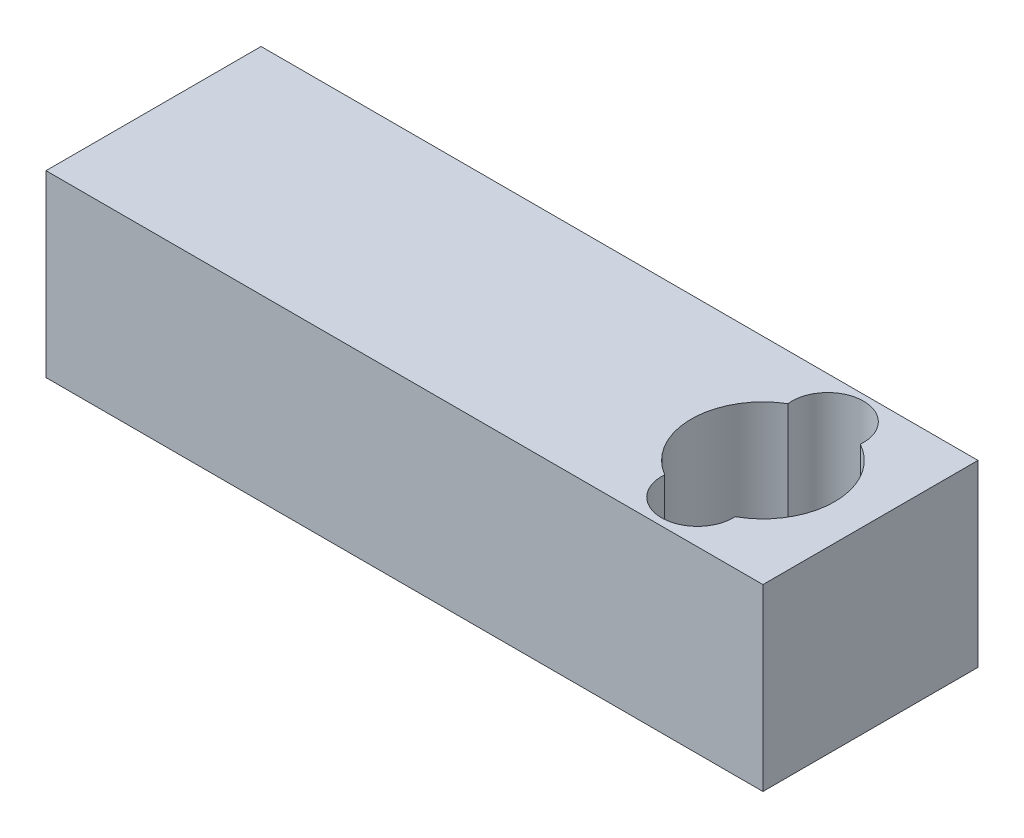
SolidWorks part; units mm, degrees
ref_plane "前视基准面" through (0, 0, 0) normal (0, 0, 1) x (1, 0, 0)
ref_plane "上视基准面" through (0, 0, 0) normal (0, 1, 0) x (1, 0, 0)
ref_plane "右视基准面" through (0, 0, 0) normal (1, 0, 0) x (0, 0, -1)
other "Configuration Table"
sketch "草图1" plane through (0, 0, 0) normal (0, 1, 0) x (1, 0, 0)
  line L1 (-50, 15) -> (50, 15)
  line L2 (-50, 15) -> (-50, -15)
  line L3 (-50, -15) -> (50, -15)
  line L4 (50, 15) -> (50, -15)
  line L5 (-50, 15) -> (50, -15) construction
  line L6 (-50, -15) -> (50, 15) construction
  circle A0 centre (35, 0) radius 10
  circle A1 centre (35, 0) radius 3
  arc A2 (29.8879, 8.5946) -> (39.8345, 8.7537) centre (34.8531, 9.184) cw
  arc A3 (29.8879, -8.5946) -> (39.8637, -8.7376) centre (34.8709, -9.0069) ccw
  point P0 (0, 0)
  point P12 (34.7731, 14.1834)
  point P16 (0, 0)
  point P17 (0, 0)
  point P18 (0, 0)
  dimension "D3" = 20
  dimension "D4" = 6
  dimension "D6" = 5
  dimension "D1" = 100
  dimension "D2" = 30
  dimension "D5" = 5
  dimension "D7" = 8.7537
  dimension "D8" = 8.5946
  dimension "D9" = 8.5946
  dimension "D10" = 8.7376
extrude "凸台-拉伸3" add sketch "草图1" along normal blind 25 contours L4 L1 L2 L3 A3 A0 A2
